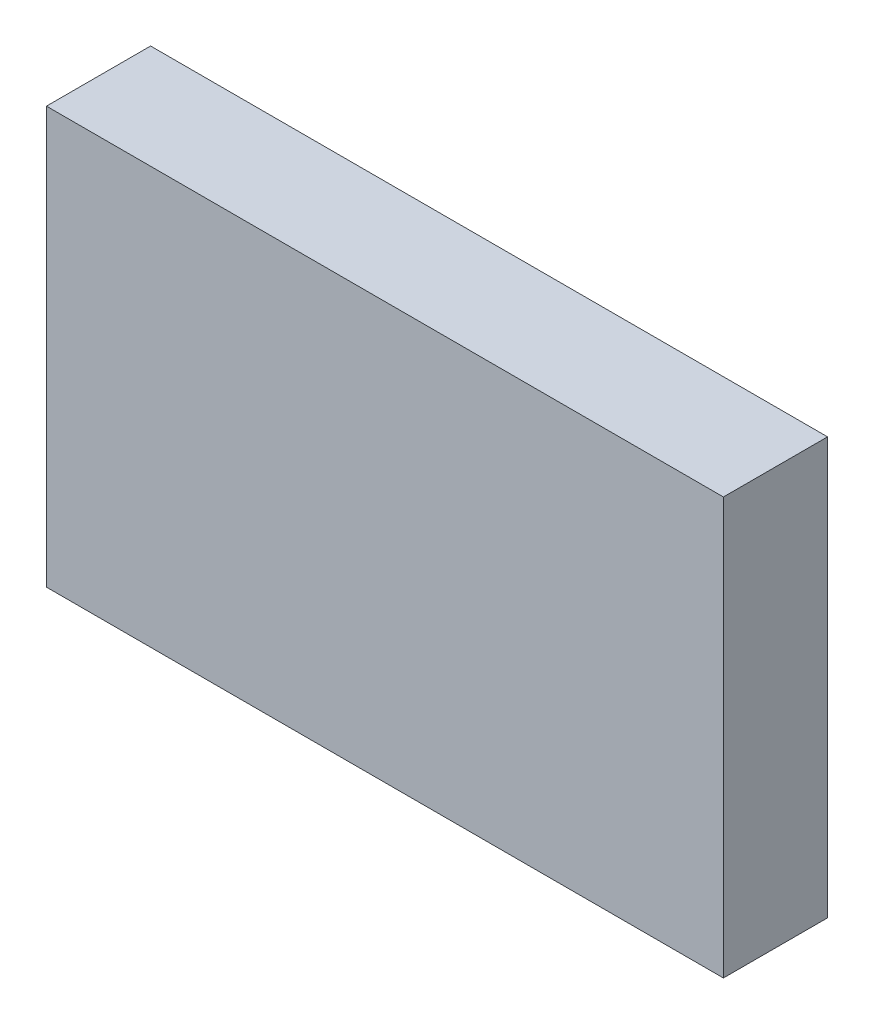
SolidWorks part; units mm, degrees
ref_plane "前视基准面" through (0, 0, 0) normal (0, 0, 1) x (1, 0, 0)
ref_plane "上视基准面" through (0, 0, 0) normal (0, 1, 0) x (1, 0, 0)
ref_plane "右视基准面" through (0, 0, 0) normal (1, 0, 0) x (0, 0, -1)
other "Configuration Table"
sketch "草图1" plane through (0, 0, 0) normal (0, 0, 1) x (1, 0, 0)
  line L0 (0, 0) -> (13, 0)
  line L1 (13, 0) -> (13, 8)
  line L2 (13, 8) -> (0, 8)
  line L3 (0, 8) -> (0, 0)
  dimension "width" = 13
  dimension "height" = 8
extrude "BlockExtrude" add sketch "草图1" along normal blind 2
